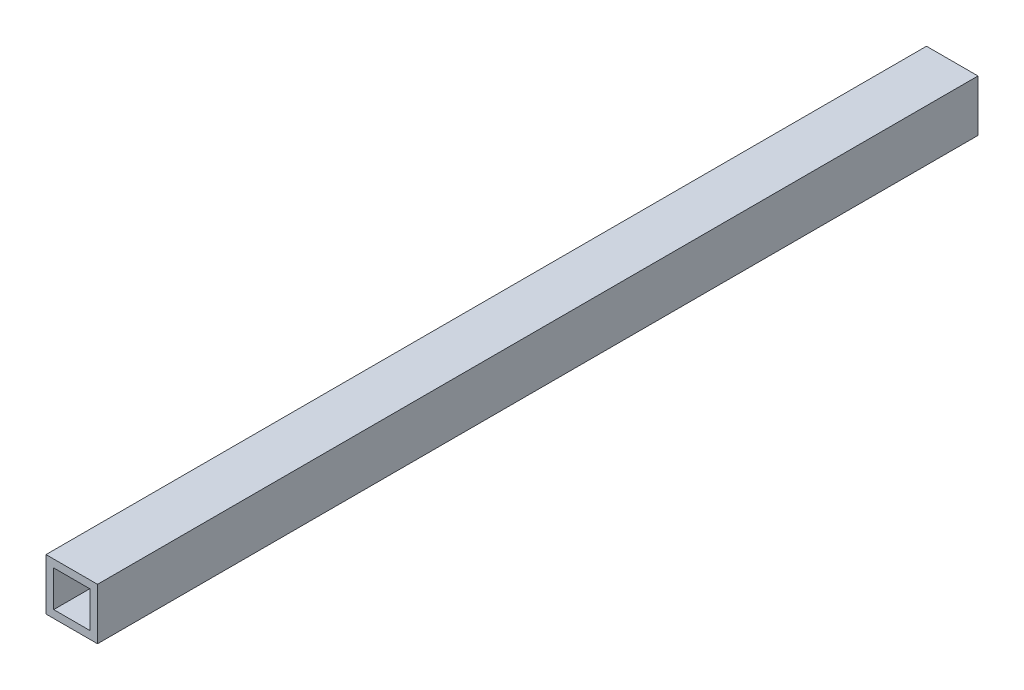
SolidWorks part; units mm, degrees
ref_plane "Plan de face" through (0, 0, 0) normal (0, 0, 1) x (1, 0, 0)
ref_plane "Plan de dessus" through (0, 0, 0) normal (0, 1, 0) x (1, 0, 0)
ref_plane "Plan de droite" through (0, 0, 0) normal (1, 0, 0) x (0, 0, -1)
sketch "Esquisse1" plane through (0, 0, 0) normal (0, 0, 1) x (1, 0, 0)
  line L1 (0, 0) -> (11.7, 0)
  line L2 (0, 0) -> (0, 11.7)
  line L3 (0, 11.7) -> (11.7, 11.7)
  line L4 (11.7, 0) -> (11.7, 11.7)
  line L5 (1.75, 1.75) -> (9.95, 1.75)
  line L6 (1.75, 1.75) -> (1.75, 9.95)
  line L7 (1.75, 9.95) -> (9.95, 9.95)
  line L8 (9.95, 1.75) -> (9.95, 9.95)
  dimension "D1" = 11.7
  dimension "D2" = 11.7
  dimension "D3" = 8.2
  dimension "D4" = 8.2
  dimension "D5" = 1.75
  dimension "D6" = 1.75
  dimension "D7" = 1.75
extrude "Boss.-Extru.1" add sketch "Esquisse1" along normal blind 200
